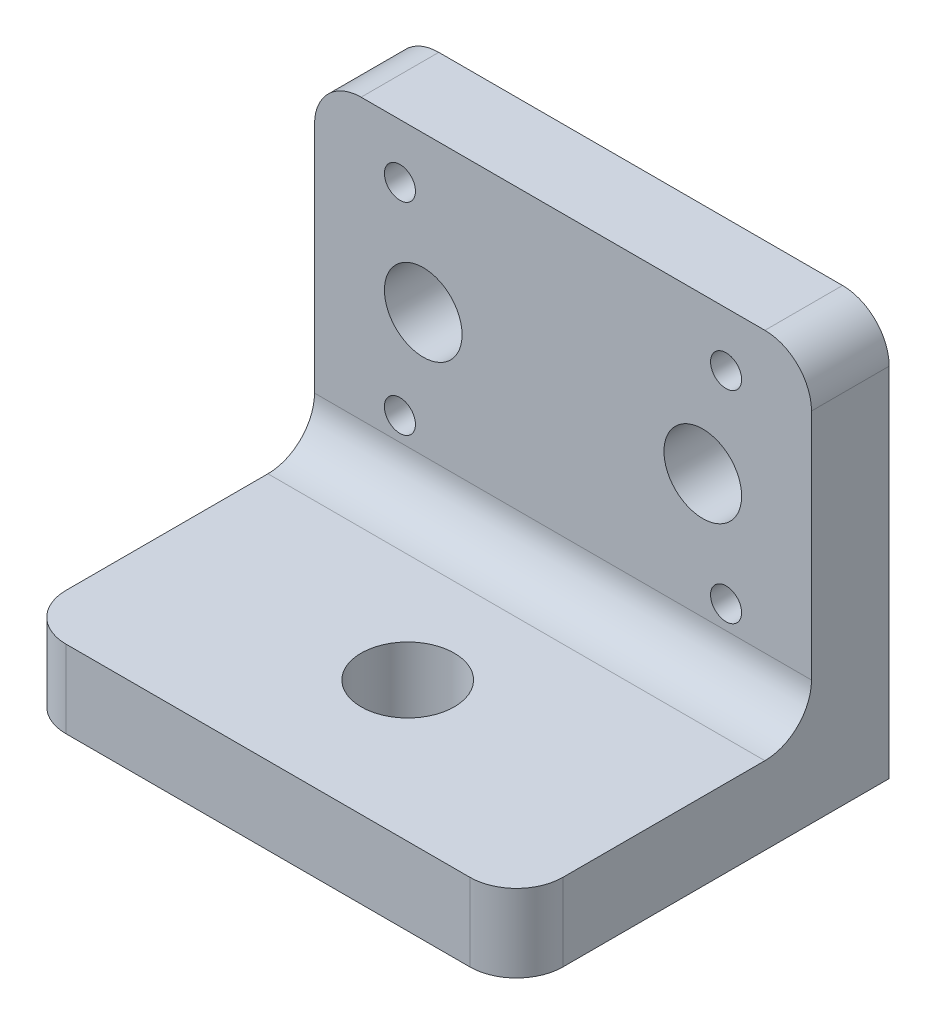
SolidWorks part; units mm, degrees
ref_plane "Front Plane" through (0, 0, 0) normal (0, 0, 1) x (1, 0, 0)
ref_plane "Top Plane" through (0, 0, 0) normal (0, 1, 0) x (1, 0, 0)
ref_plane "Right Plane" through (0, 0, 0) normal (1, 0, 0) x (0, 0, -1)
sketch "Sketch1" plane through (0, 0, 0) normal (0, 0, 1) x (1, 0, 0)
  line L1 (-16, 16) -> (16, 16)
  line L2 (-16, 16) -> (-16, -16)
  line L3 (-16, -16) -> (16, -16)
  line L4 (16, 16) -> (16, -16)
  point P4 (0, 16)
  point P6 (-16, 0)
  dimension "D1" = 32
  dimension "D2" = 32
extrude "Boss-Extrude1" add sketch "Sketch1" along normal blind 5
hole_wizard "Ø5.0mm Dowel Hole1" positions "Sketch2" profile "Sketch3" hole size "Ø5.0" standard "ANSI Metric" end condition up to next
sketch "Sketch2" plane through (0, 0, 5) normal (0, 0, 1) x (1, 0, 0)
  line L0 (-9, 0) -> (9, 0) construction
  line L2 (0, -55) -> (0, 55) construction
  point P0 (-9, 0)
  point P2 (9, 0)
  point P9 (0, 0)
  dimension "D1" = 18
sketch "Sketch3" plane through (-9, 0, 5) normal (1, 0, 0) x (0, -1, 0)
  line L0 (0, 0) -> (0, 5)
  line L1 (0, 5) -> (2.5, 5)
  line L2 (2.5, 5) -> (2.5, 0)
  line L5 (2.5, 0) -> (0, 0)
  line L11 (0, -6.35) -> (0, 107.95) construction
  dimension "Thru Hole Dia." = 5
  dimension "Thru Hole Depth" = 5
hole_wizard "Ø2.0mm Dowel Hole1" positions "Sketch4" profile "Sketch5" hole size "Ø2.0" standard "ANSI Metric" end condition up to next
sketch "Sketch4" plane through (0, 0, 5) normal (0, 0, 1) x (1, 0, 0)
  line L0 (-10.5, 6.5) -> (10.5, 6.5) construction
  line L1 (10.5, 6.5) -> (10.5, -6.5) construction
  point P0 (-10.5, 6.5)
  point P12 (10.5, 6.5)
  point P14 (10.5, -6.5)
  point P16 (-10.5, -6.5)
  point P27 (10.5, 0)
  point P30 (0, 6.5)
  dimension "D1" = 21
  dimension "D2" = 13
sketch "Sketch5" plane through (-10.5, 6.5, 5) normal (1, 0, 0) x (0, -1, 0)
  line L0 (0, 0) -> (0, 5)
  line L1 (0, 5) -> (1, 5)
  line L2 (1, 5) -> (1, 0)
  line L5 (1, 0) -> (0, 0)
  line L11 (0, -6.35) -> (0, 107.95) construction
  dimension "Thru Hole Dia." = 2
  dimension "Thru Hole Depth" = 5
sketch "Sketch11" plane through (0, 0, 5) normal (0, 0, 1) x (1, 0, 0)
  line L0 (16, -16) -> (16, 16) construction
  line L1 (-16, -16) -> (16, -16)
  line L2 (-16, -16) -> (-16, -11)
  line L3 (-16, -11) -> (16, -11)
  line L4 (16, -16) -> (16, -11)
  dimension "D1" = 5
extrude "Boss-Extrude3" add sketch "Sketch11" along normal blind 19
hole_wizard "Ø6.0mm Dowel Hole1" positions "Sketch12" profile "Sketch13" hole size "Ø6.0" standard "ANSI Metric" end condition up to next
sketch "Sketch12" plane through (0, -11, 0) normal (0, 1, 0) x (1, 0, 0)
  line L0 (16, 0) -> (-16, 0) construction
  point P0 (0, -15)
  dimension "D1" = 15
sketch "Sketch13" plane through (0, -11, 15) normal (1, 0, 0) x (0, 0, 1)
  line L0 (0, 0) -> (0, 5)
  line L1 (0, 5) -> (3, 5)
  line L2 (3, 5) -> (3, 0)
  line L5 (3, 0) -> (0, 0)
  line L11 (0, -6.35) -> (0, 107.95) construction
  dimension "Thru Hole Dia." = 6
  dimension "Thru Hole Depth" = 5
sketch "Sketch14" plane through (0, 16, 0) normal (0, 1, 0) x (1, 0, 0)
  line L4 (16, 0) -> (-16, 0)
  line L5 (-16, 0) -> (-16, -5)
  line L6 (-16, -5) -> (16, -5)
  line L7 (16, -5) -> (16, 0)
  line L8 (16, 0) -> (-16, 0)
  line L9 (-16, 0) -> (-16, -5)
  line L10 (-16, -5) -> (16, -5)
  line L11 (16, -5) -> (16, 0)
  dimension "D1" = 0
extrude "Cut-Extrude1" cut sketch "Sketch14" against normal blind 6
fillet "Fillet3" radius 3 5 edges at (16, 10, 2.5) (-16, 10, 2.5) (-16, -13.5, 24) (16, -13.5, 24) (0, -11, 5)
